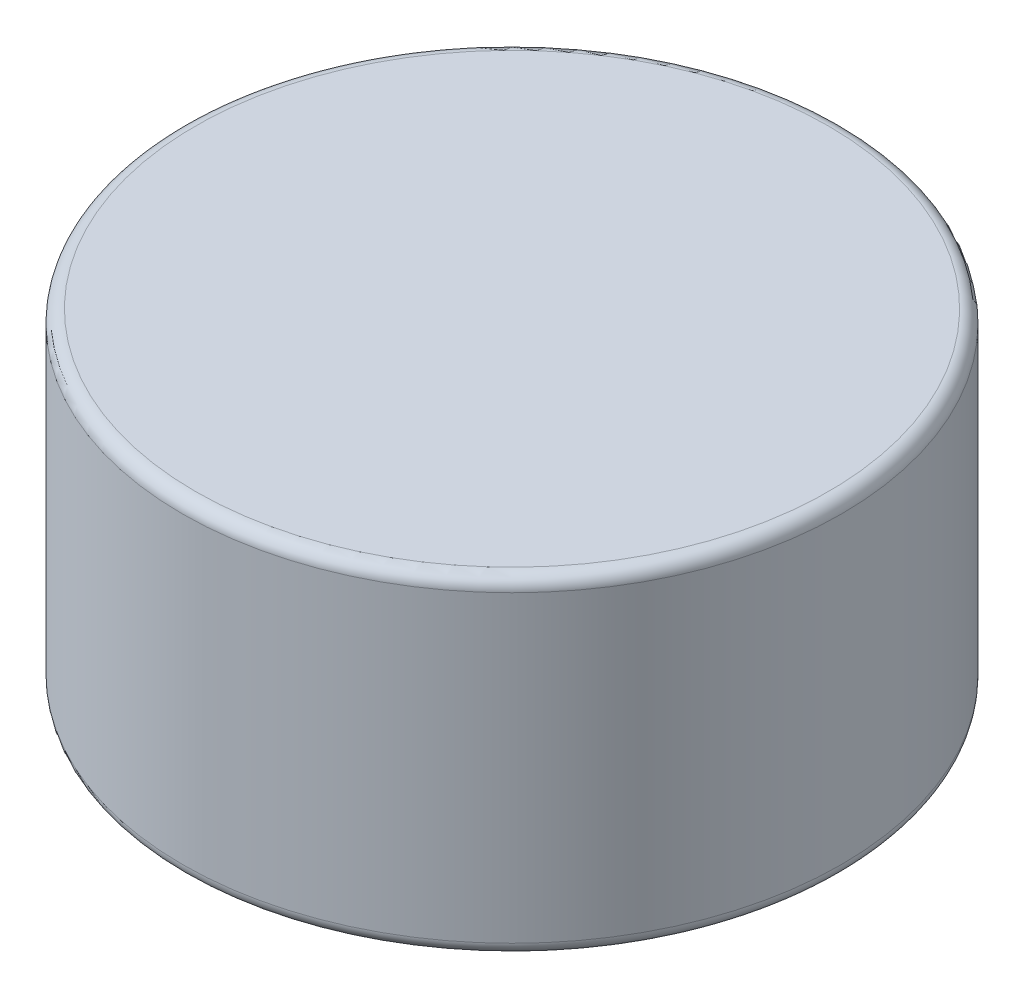
SolidWorks part; units mm, degrees
material "Neodymium"
ref_plane "Front Plane" through (0, 0, 0) normal (0, 0, 1) x (1, 0, 0)
ref_plane "Top Plane" through (0, 0, 0) normal (0, 1, 0) x (1, 0, 0)
ref_plane "Right Plane" through (0, 0, 0) normal (1, 0, 0) x (0, 0, -1)
sketch "Sketch1" plane through (0, 0, 0) normal (0, 1, 0) x (1, 0, 0)
  circle A0 centre (0, 0) radius 12.7
  dimension "D1" = 25.4
extrude "Boss-Extrude1" add sketch "Sketch1" along normal mid plane 12.7
fillet "Fillet1" radius 0.5 2 edges at (0, -6.35, 12.7) (0, 6.35, 12.7)
